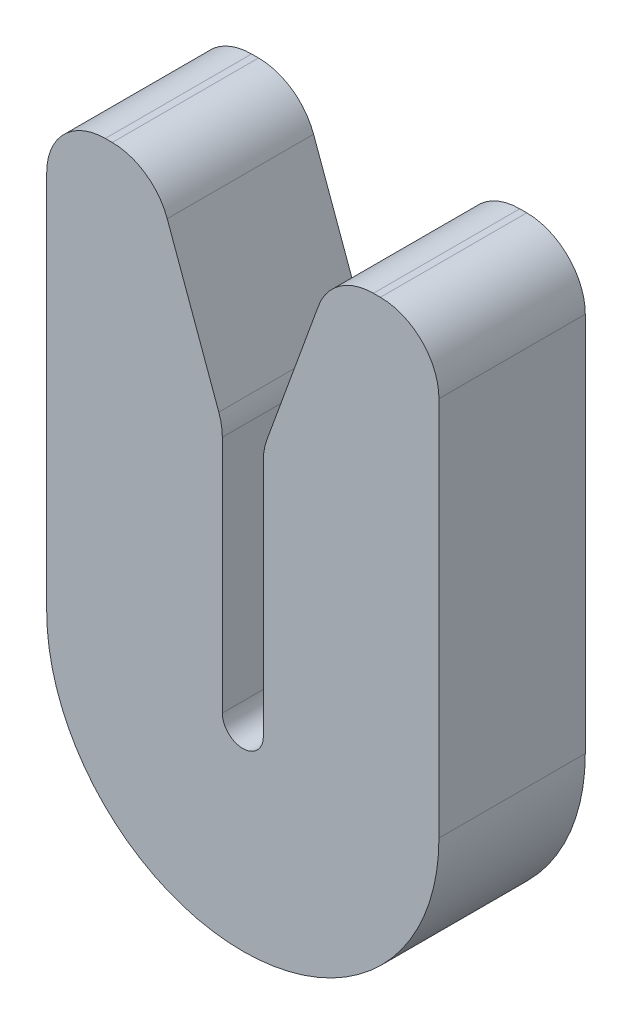
SolidWorks part; units mm, degrees
ref_plane "Front Plane" through (0, 0, 0) normal (0, 0, 1) x (1, 0, 0)
ref_plane "Top Plane" through (0, 0, 0) normal (0, 1, 0) x (1, 0, 0)
ref_plane "Right Plane" through (0, 0, 0) normal (1, 0, 0) x (0, 0, -1)
sketch "Sketch1" plane through (0, 0, 0) normal (0, 0, 1) x (1, 0, 0)
  line L0 (0, 0) -> (0, 3.828) construction
  line L1 (-0.7, 0) -> (-0.7, 8.511)
  line L3 (-6.7, 15) -> (-6.7, 0)
  line L4 (0.7, 0) -> (0.7, 8.511)
  line L6 (6.7, 15) -> (6.7, 0)
  line L7 (-7.4577, 15) -> (-6.7, 15) construction
  line L8 (-6.7, 15) -> (-3.0618, 15)
  line L9 (3.0618, 15) -> (6.7, 15)
  line L10 (-3.0618, 15) -> (-0.7, 8.511)
  line L11 (0.7, 8.511) -> (3.0618, 15)
  arc A0 (-0.7, 0) -> (0.7, 0) centre (0, 0) ccw
  arc A1 (-6.7, 0) -> (6.7, 0) centre (0, 0) ccw
  dimension "D1" = 0.7
  dimension "D2" = 160
  dimension "D3" = 6
  dimension "D6" = 15
extrude "Boss-Extrude1" add sketch "Sketch1" along normal blind 5
fillet "Fillet2" radius 2 6 edges at (6.7, 15, 2.5) (-6.7, 15, 2.5) (-3.0618, 15, 2.5) (3.0618, 15, 2.5) (0.7, 8.511, 2.5) (-0.7, 8.511, 2.5)
